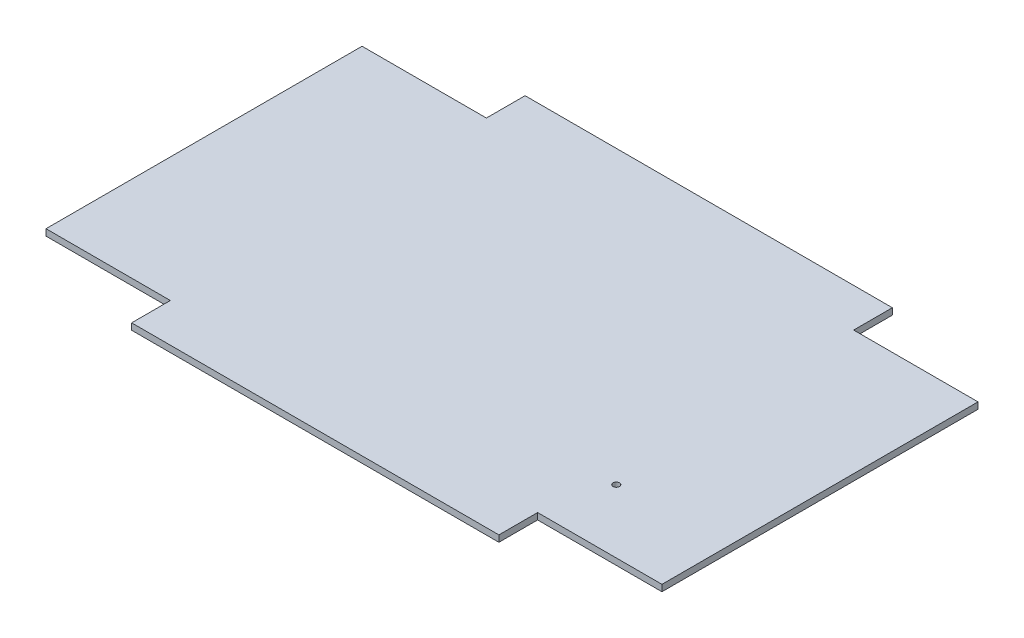
SolidWorks part; units mm, degrees
ref_plane "Front Plane" through (0, 0, 0) normal (0, 0, 1) x (1, 0, 0)
ref_plane "Top Plane" through (0, 0, 0) normal (0, 1, 0) x (1, 0, 0)
ref_plane "Right Plane" through (0, 0, 0) normal (1, 0, 0) x (0, 0, -1)
sketch "Sketch1" plane through (0, 0, 0) normal (0, 1, 0) x (1, 0, 0)
  line L0 (122.428, 0) -> (122.428, -38.1)
  line L1 (0, 311.15) -> (606.425, 311.15) construction
  line L2 (0, 311.15) -> (0, 0)
  line L3 (0, 0) -> (606.425, 0) construction
  line L4 (606.425, 311.15) -> (606.425, 0)
  line L5 (122.428, -38.1) -> (483.997, -38.1)
  line L6 (483.997, -38.1) -> (483.997, 0)
  line L7 (122.428, 311.15) -> (122.428, 349.25)
  line L8 (122.428, 349.25) -> (483.997, 349.25)
  line L9 (483.997, 349.25) -> (483.997, 311.15)
  line L10 (0, 311.15) -> (122.428, 311.15)
  line L11 (483.997, 311.15) -> (606.425, 311.15)
  line L12 (606.425, 0) -> (483.997, 0)
  line L13 (122.428, 0) -> (0, 0)
  point P7 (303.2125, -38.1)
  point P10 (303.2125, 349.25)
  point P11 (303.2125, 0)
  point P16 (303.2125, 311.15)
  dimension "D1" = 311.15
  dimension "D2" = 606.425
  dimension "D3" = 122.428
  dimension "D4" = 38.1
  dimension "D5" = 38.1
extrude "Boss-Extrude1" add sketch "Sketch1" along normal blind 6.35
sketch "Sketch2" plane through (0, 6.35, 0) normal (0, 1, 0) x (1, 0, 0)
  line L0 (606.425, 0) -> (606.425, 311.15) construction
  line L2 (483.997, 0) -> (606.425, 0) construction
  circle A0 centre (498.983, 62.484) radius 3.175
  dimension "D3" = 6.35
  dimension "D1" = 107.442
  dimension "D2" = 62.484
extrude "Cut-Extrude1" cut sketch "Sketch2" against normal through all
